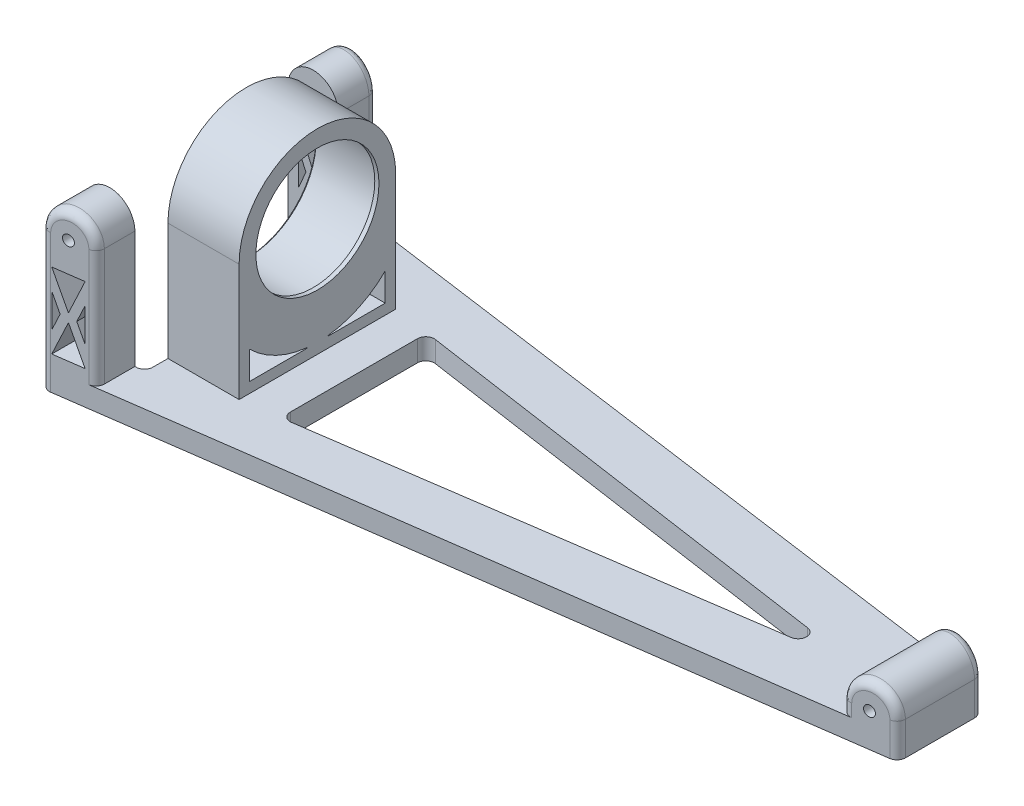
SolidWorks part; units mm, degrees
ref_plane "Front Plane" through (0, 0, 0) normal (0, 0, 1) x (1, 0, 0)
ref_plane "Top Plane" through (0, 0, 0) normal (0, 1, 0) x (1, 0, 0)
ref_plane "Right Plane" through (0, 0, 0) normal (1, 0, 0) x (0, 0, -1)
sketch "Sketch1" plane through (0, 0, 0) normal (0, 1, 0) x (1, 0, 0)
  line L0 (0, -35) -> (0, 35)
  line L13 (180, -10) -> (180, 10)
  line L14 (0, -35) -> (180, -10)
  line L19 (180, 10) -> (0, 35)
  point P3 (0, 0)
  point P6 (180, 0)
  dimension "D1" = 20
  dimension "D2" = 70
  dimension "D3" = 180
extrude "Boss-Extrude1" add sketch "Sketch1" along normal blind 5
sketch "Sketch2" plane through (0, 0, 0) normal (0, 0, 1) x (1, 0, 0)
  line L0 (0, 5) -> (180, 5) construction
  line L1 (0, 5) -> (180, 5)
  line L2 (0, 5) -> (0, 33)
  line L3 (12, 5) -> (12, 33)
  line L4 (180, 5) -> (180, 8)
  line L5 (168, 5) -> (168, 8)
  line L6 (2.5, 26) -> (9.5, 26)
  line L7 (9.5, 26) -> (6, 18)
  line L8 (6, 18) -> (2.5, 26)
  line L9 (6, 16) -> (2.5, 8)
  line L10 (2.5, 8) -> (9.5, 8)
  line L11 (9.5, 8) -> (6, 16)
  line L12 (2.5, 21.0102) -> (2.5, 12.9898)
  line L13 (2.5, 12.9898) -> (4.2545, 17)
  line L14 (4.2545, 17) -> (2.5, 21.0102)
  line L15 (9.5, 21.0102) -> (9.5, 12.9898)
  line L16 (9.5, 12.9898) -> (7.7455, 17)
  line L17 (7.7455, 17) -> (9.5, 21.0102)
  line L18 (6, 18) -> (6, 16) construction
  arc A0 (0, 33) -> (12, 33) centre (6, 33) cw
  circle A2 centre (174, 8) radius 1.25
  arc A3 (168, 8) -> (180, 8) centre (174, 8) cw
  circle A4 centre (6, 33) radius 1.25
  point P26 (6, 17)
  dimension "D1" = 28
  dimension "D2" = 6
  dimension "D4" = 3
  dimension "D3" = 2.5
  dimension "D5" = 18
  dimension "D6" = 3
  dimension "D7" = 8
  dimension "D8" = 7
  dimension "D9" = 2
extrude "Boss-Extrude2" add sketch "Sketch2" along normal up to surface and the other way up to surface
sketch "Sketch4" plane through (0, 0, 0) normal (0, 1, 0) x (1, 0, 0)
  line L1 (0, 24.3) -> (14.3, 24.3)
  line L2 (0, 24.3) -> (0, -24.3)
  line L3 (0, -24.3) -> (14.3, -24.3)
  line L4 (14.3, 24.3) -> (14.3, -24.3)
  line L5 (0, -35) -> (0, 35) construction
  point P6 (14.3, 0)
  dimension "D1" = 48.6
  dimension "D2" = 14.3
extrude "Cut-Extrude1" cut sketch "Sketch4" along normal through all both and the other way through all
sketch "Sketch5" plane through (14.3, 0, 0) normal (-1, 0, 0) x (0, 0, 1)
  line L0 (-18.7, 5) -> (-18.7, 33)
  line L1 (-24.3, 5) -> (24.3, 5) construction
  line L2 (18.7, 5) -> (18.7, 33)
  line L3 (18.7, 5) -> (-18.7, 5)
  line L7 (16.2, 7.5) -> (16.2, 14.1733)
  line L8 (16.2, 7.5) -> (2.5, 7.5)
  line L9 (-16.2, 7.5) -> (-16.2, 14.1733)
  line L10 (-16.2, 7.5) -> (-16.2, 33) construction
  line L11 (16.2, 7.5) -> (16.2, 33) construction
  line L12 (-2.5, 7.6363) -> (-2.5, 7.5)
  line L13 (-2.5, 7.5) -> (-16.2, 7.5)
  line L14 (2.5, 7.6363) -> (2.5, 7.5)
  line L15 (16.2, 7.5) -> (-16.2, 7.5) construction
  arc A0 (-18.7, 33) -> (18.7, 33) centre (0, 33) cw
  circle A1 centre (0, 33) radius 16.2
  arc A3 (-16.2, 14.1733) -> (-2.5, 7.6363) centre (0, 30.5) ccw
  arc A4 (2.5, 7.6363) -> (16.2, 14.1733) centre (0, 30.5) ccw
  ellipse E1 centre (-34.1667, 33) end of major axis (-34.1667, 34.25) minor radius 0.1736 construction
  ellipse E2 centre (-34.1667, 33) end of major axis (-34.1667, 34.25) minor radius 0.1736
  point P6 (0, 5)
  point P29 (2.5, 7.5681)
  line M9 (24.3, 5) -> (-24.3, 5)
  dimension "D3" = 32.4
  dimension "D2" = 2.5
  dimension "D1" = 2.5
  dimension "D4" = 2.5
  dimension "D5" = 5
extrude "Boss-Extrude3" add sketch "Sketch5" against normal blind 16.5 contours A1 L2 A0 L0 M9
sketch "Sketch7" plane through (30.8, 0, 0) normal (1, 0, 0) x (0, 0, -1)
  line L9 (-18.7, 33) -> (-18.7, 5)
  line L10 (-18.7, 5) -> (18.7, 5)
  line L11 (18.7, 5) -> (18.7, 33)
  line L12 (-18.7, 33) -> (-18.7, 5)
  line L13 (-18.7, 5) -> (18.7, 5)
  line L14 (18.7, 5) -> (18.7, 33)
  arc A3 (18.7, 33) -> (-18.7, 33) centre (0, 33) ccw
  arc A4 (18.7, 33) -> (-18.7, 33) centre (0, 33) ccw
  circle A7 centre (0, 33) radius 14.7
  circle A8 centre (0, 33) radius 14.7
  circle M6 centre (0, 33) radius 16.2
  arc M7 (18.7, 33) -> (-18.7, 33) centre (0, 33) ccw
  line M8 (-18.7, 33) -> (-18.7, 5)
  line M10 (18.7, 5) -> (18.7, 33)
  line M12 (-18.7, 5) -> (18.7, 5)
  line M15 (16.2, 14.1733) -> (16.2, 7.5)
  line M16 (-2.5, 7.5) -> (-16.2, 7.5)
  line M17 (-16.2, 7.5) -> (-16.2, 14.1733)
  line M18 (16.2, 7.5) -> (2.5, 7.5)
  line M19 (2.5, 7.5) -> (2.5, 7.6363)
  arc M20 (2.5, 7.6363) -> (16.2, 14.1733) centre (0, 30.5) ccw
  line M21 (-2.5, 7.6363) -> (-2.5, 7.5)
  arc M22 (-16.2, 14.1733) -> (-2.5, 7.6363) centre (0, 30.5) ccw
  dimension "D1" = 0
  dimension "D2" = 1.5
extrude "Boss-Extrude5" add sketch "Sketch7" along normal mid plane 1 contours M10 M7 M8 M12 M22 M21 M16 M17 M20 M15 M18 M19 M6 | A8 M6
sketch "Sketch8" plane through (0, 5, 0) normal (0, 1, 0) x (1, 0, 0)
  line L0 (40, 17.5) -> (40, -17.5)
  line L1 (40, -17.5) -> (160, 0)
  line L2 (160, 0) -> (40, 17.5)
  point P4 (40, 0)
  dimension "D1" = 40
  dimension "D2" = 120
  dimension "D3" = 35
extrude "Cut-Extrude2" cut sketch "Sketch8" against normal through all
fillet "Fillet2" radius 2 3 edges at (160, 2.5, 0) (40, 2.5, 17.5) (40, 2.5, -17.5)
fillet "Fillet5" radius 2 2 edges at (14.3, 2.5, 24.3) (14.3, 2.5, -24.3)
chamfer "Chamfer1" distance 0.5 angle 45 1 edges at (14.3, 33, 16.2)
fillet "Fillet6" radius 2 12 edges at (180, 4, -10) (168, 6.5, -11.6667) (180, 4, 10) (168, 6.5, 11.6667) (12, 19, -33.3333) (0, 16.5, -35) (12, 19, 33.3333) (0, 16.5, 35) (174, 14, -10.8333) (174, 14, 10.8333) (6, 39, -34.1667) (6, 39, 34.1667)
